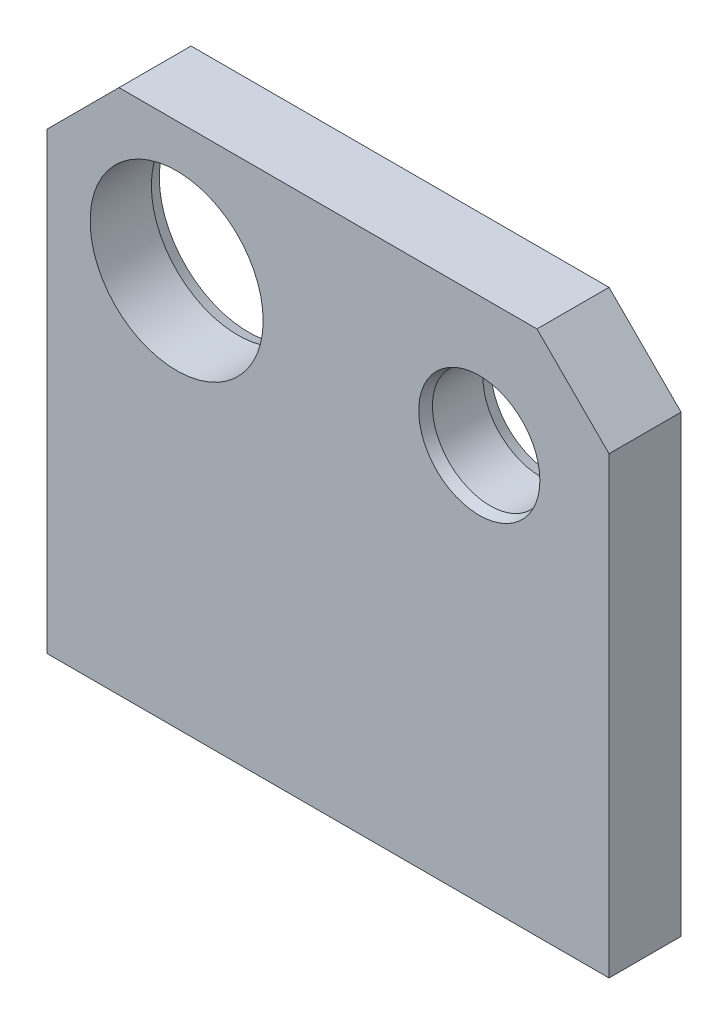
SolidWorks part; units mm, degrees
material "Plain Carbon Steel"
ref_plane "Front Plane" through (0, 0, 0) normal (0, 0, 1) x (1, 0, 0)
ref_plane "Top Plane" through (0, 0, 0) normal (0, 1, 0) x (1, 0, 0)
ref_plane "Right Plane" through (0, 0, 0) normal (1, 0, 0) x (0, 0, -1)
sketch "Sketch1" plane through (0, 0, 0) normal (0, 0, 1) x (1, 0, 0)
  line L1 (0, 0) -> (78, 0)
  line L2 (0, 0) -> (0, 73)
  line L3 (0, 73) -> (78, 73)
  line L4 (78, 0) -> (78, 73)
  dimension "Dim B" = 78
  dimension "Dim A" = 73
extrude "Extrude1" add sketch "Sketch1" along normal blind 10
sketch "Sketch3" plane through (0, 0, 10) normal (0, 0, 1) x (1, 0, 0)
  line L0 (0, 73) -> (0, 0) construction
  line L2 (0, 0) -> (78, 0) construction
  circle A0 centre (18, 55) radius 12.0065
  dimension "D1" = 24.013
  dimension "D3" = 18
  dimension "Dim D" = 55
extrude "24dia Hole" cut sketch "Sketch3" against normal through all
hole_wizard "M6 Tapped Hole1" positions "3DSketch1" profile "Sketch6" tap size "M6" standard "DIN"
sketch3d "3DSketch1"
  line L0 (0, 0, 10) -> (0, 0, 0) construction
  line L2 (0, 0, 0) -> (78, 0, 0) construction
  point P0 (5, 0, 5)
  point P2 (73, 0, 5)
  point P11 (-3.4686, 0, 3.0785)
  dimension "D1" = 5
  dimension "D3" = 5
  dimension "Dim E" = 68
sketch "Sketch6" plane through (5, 0, 5) normal (1, 0, 0) x (0, 0, -1)
  line L0 (0, 0) -> (0, 16.5022)
  line L1 (0, 16.5022) -> (2.5, 15)
  line L2 (2.5, 15) -> (2.5, 0)
  line L5 (2.5, 0) -> (0, 0)
  line L10 (0, 16.5022) -> (-2.5, 15) construction
  line L11 (0, -6.35) -> (0, 107.95) construction
  dimension "Tap Drill Dia." = 5
  dimension "Tap Drill Depth" = 15
  dimension "Drill Angle" = 118
cosmetic thread "Hole Thread1" parameters "D1"=12, "D2"=6
cosmetic thread "Hole Thread2" parameters "D1"=12, "D2"=6
cosmetic thread "Hole Thread3" parameters "D1"=12, "D2"=6
sketch "Sketch7" plane through (0, 0, 10) normal (0, 0, 1) x (1, 0, 0)
  line L0 (0, 0) -> (78, 0) construction
  circle A0 centre (60, 55) radius 8.0045
  circle A1 centre (18, 55) radius 12.0065 construction
  dimension "D1" = 16.009
  dimension "Dim C" = 42
  dimension "Dim D" = 55
extrude "16dia hole" cut sketch "Sketch7" against normal through all
chamfer "Chamfer1" distance 10 angle 45 2 edges at (0, 73, 5) (78, 73, 5)
chamfer "Chamfer2" distance 1.5 angle 15 2 edges at (68.0045, 55, 0) (30.0065, 55, 0)
chamfer "Chamfer3" distance 1.5 angle 15 1 edges at (68.0045, 55, 10)
equation "\"Dim B@Sketch1\" = \"Dim C@Sketch7\" + 36"
equation "\"Dim A@Sketch1\" = \"Dim D@Sketch3\" + 18"
equation "\"Dim E@3DSketch1\" = \"Dim C@Sketch7\" + 26"
